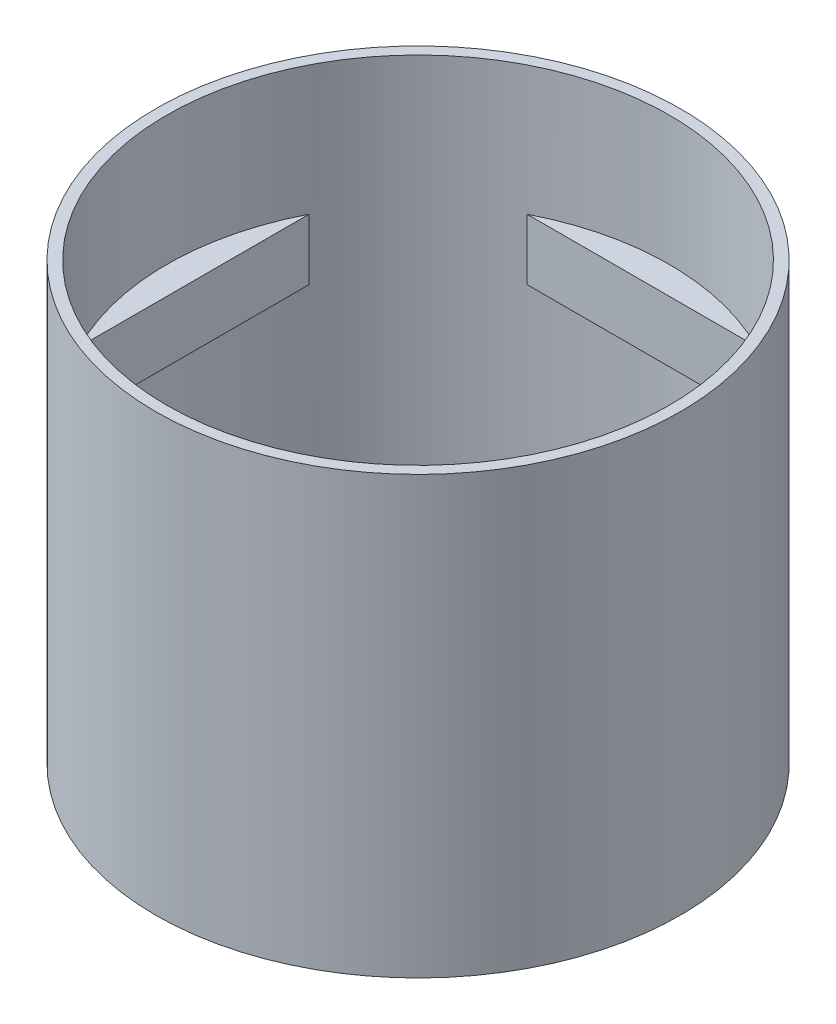
SolidWorks part; units mm, degrees
ref_plane "前基準面" through (0, 0, 0) normal (0, 0, 1) x (1, 0, 0)
ref_plane "上基準面" through (0, 0, 0) normal (0, 1, 0) x (1, 0, 0)
ref_plane "右基準面" through (0, 0, 0) normal (1, 0, 0) x (0, 0, -1)
sketch "草圖1" plane through (0, 0, 0) normal (0, 1, 0) x (1, 0, 0)
  line L0 (0, 78.355) -> (0, -92.3476) construction
  line L1 (-97.6496, 0) -> (95.3358, 0) construction
  line L3 (-34, 34) -> (34, 34) construction
  line L4 (-34, 34) -> (-34, -34) construction
  line L5 (-34, -34) -> (34, -34) construction
  line L6 (34, 34) -> (34, -34) construction
  line L7 (-34, 34) -> (34, -34) construction
  line L20 (45.5449, 45.5449) -> (-45.5449, -45.5449) construction
  circle A0 centre (0, 0) radius 72.25
  circle A1 centre (0, 0) radius 71
  circle A2 centre (0, 0) radius 68
  circle A4 centre (0, 0) radius 73 construction
  point P7 (0, 0)
  point P12 (-30, 30)
  point P14 (30, 30)
  point P17 (30, -30)
  point P18 (-30, -30)
  point P19 (0, 0)
  point P23 (-73, 0)
  point P24 (-72.25, 0)
  point P25 (-71, 0)
  point P26 (34, 0)
  point P27 (-34, 0)
  point P28 (-68, 0)
  dimension "D1" = 144.5
  dimension "D5" = 142
  dimension "D6" = 3
  dimension "D8" = 146
  dimension "D2" = 68
  dimension "D3" = 4
  dimension "D4" = 4
sketch "草圖4" plane through (0, 0, 0) normal (0, 0, 1) x (1, 0, 0)
  line L0 (-34, 0) -> (-34, 118)
  line L1 (73, 0) -> (-73, 0) construction
  line L3 (34, 0) -> (36.5756, 118)
  line L4 (36.5756, 118) -> (-34, 118)
  line L5 (-34, 0) -> (34, 0)
  line L6 (-34, 15) -> (34.3274, 15)
  line L7 (-34, 16.5) -> (34.3601, 16.5)
  line L8 (-34, 31.5) -> (34.6876, 31.5)
  line L9 (-34, 33) -> (34.7203, 33)
  line L10 (-34, 48) -> (35.0477, 48)
  line L11 (-34, 49.5) -> (35.0804, 49.5)
  line L12 (-34, 66.5) -> (35.4515, 66.5)
  line L13 (-34, 68) -> (35.4843, 68)
  line L14 (-34, 83) -> (35.8117, 83)
  line L15 (-34, 85) -> (35.8553, 85)
  line L16 (-34, 101.5) -> (36.2155, 101.5)
  line L17 (-34, 103) -> (36.2482, 103)
  line L18 (-72.25, 0) -> (-72.25, 145.0993)
  line L19 (-68, 0) -> (-68, 146.8435)
  line L20 (-30, 0) -> (-30, 145.404) construction
  line L21 (-31.5, 118) -> (-31.5, 124) construction
  line L22 (-31.5, 124) -> (-28.5, 124) construction
  line L23 (-28.5, 124) -> (-28.5, 118) construction
  line L24 (-34, 86.5) -> (35.8881, 86.5)
  line L25 (-34, 64.5) -> (35.4079, 64.5)
  point P40 (-30, 124)
  dimension "D1" = 1.5
  dimension "D2" = 15
  dimension "D3" = 1.5
  dimension "D4" = 1.5
  dimension "D5" = 1.5
  dimension "D6" = 15
  dimension "D7" = 15
  dimension "D8" = 15
  dimension "D9" = 2
  dimension "D10" = 15
  dimension "D11" = 1.5
  dimension "D12" = 15
  dimension "D13" = 15
  dimension "D14" = 3
  dimension "D15" = 6
  dimension "D16" = 1.5
  dimension "D17" = 83
  dimension "D18" = 2
  dimension "D19" = 118
sketch "草圖5" plane through (0, 0, 0) normal (0, 1, 0) x (1, 0, 0)
  line L0 (-60.5191, 11) -> (-50.0191, 11) construction
  line L1 (-50.0191, 11) -> (-50.0191, -11) construction
  line L2 (-50.0191, -11) -> (-60.5191, -11) construction
  line L3 (-60.5191, -11) -> (-60.5191, 11)
  line L4 (-60.5191, 8.25) -> (-70.5191, 8.25) construction
  line L6 (-70.5191, -8.25) -> (-60.5191, -8.25) construction
  line L7 (-97.6496, 0) -> (95.3358, 0) construction
  line L8 (-60.5191, 8.25) -> (-60.5191, -8.25) construction
  line L9 (-34, 34) -> (34, -34) construction
  line L10 (0, 0) -> (-19.3715, 0) construction
  line L12 (-70.5191, 8.25) -> (-70.5191, -8.25) construction
  line L13 (-60.5191, 8.25) -> (-60.5191, 31.0072)
  line L14 (-60.5191, -8.25) -> (-60.5191, -31.0072)
  line L15 (8.25, 60.5191) -> (8.25, 70.5191) construction
  line L16 (-8.25, 70.5191) -> (-8.25, 60.5191) construction
  line L17 (8.25, 60.5191) -> (31.0072, 60.5191)
  line L18 (-8.25, 60.5191) -> (-31.0072, 60.5191)
  line L19 (11, 60.5191) -> (11, 50.0191) construction
  line L20 (11, 50.0191) -> (-11, 50.0191) construction
  line L21 (-11, 50.0191) -> (-11, 60.5191) construction
  line L22 (-11, 60.5191) -> (11, 60.5191)
  line L23 (8.25, 60.5191) -> (-8.25, 60.5191) construction
  line L24 (8.25, 70.5191) -> (-8.25, 70.5191) construction
  line L25 (60.5191, -8.25) -> (70.5191, -8.25) construction
  line L26 (70.5191, 8.25) -> (60.5191, 8.25) construction
  line L27 (60.5191, -8.25) -> (60.5191, -31.0072)
  line L28 (60.5191, 8.25) -> (60.5191, 31.0072)
  line L29 (60.5191, -11) -> (50.0191, -11) construction
  line L30 (50.0191, -11) -> (50.0191, 11) construction
  line L31 (50.0191, 11) -> (60.5191, 11) construction
  line L32 (60.5191, 11) -> (60.5191, -11)
  line L33 (60.5191, -8.25) -> (60.5191, 8.25) construction
  line L34 (70.5191, -8.25) -> (70.5191, 8.25) construction
  line L35 (-8.25, -60.5191) -> (-8.25, -70.5191) construction
  line L36 (8.25, -70.5191) -> (8.25, -60.5191) construction
  line L37 (-8.25, -60.5191) -> (-31.0072, -60.5191)
  line L38 (8.25, -60.5191) -> (31.0072, -60.5191)
  line L39 (-11, -60.5191) -> (-11, -50.0191) construction
  line L40 (-11, -50.0191) -> (11, -50.0191) construction
  line L41 (11, -50.0191) -> (11, -60.5191) construction
  line L42 (11, -60.5191) -> (-11, -60.5191)
  line L43 (-8.25, -60.5191) -> (8.25, -60.5191) construction
  line L44 (-8.25, -70.5191) -> (8.25, -70.5191) construction
  circle A0 centre (0, 0) radius 68 construction
  circle A1 centre (0, 0) radius 72.25 construction
  arc A2 (-31.0072, 60.5191) -> (-60.5191, 31.0072) centre (0, 0) ccw
  circle A3 centre (0, 0) radius 68
  arc A5 (-60.5191, -31.0072) -> (-31.0072, -60.5191) centre (0, 0) ccw
  circle A6 centre (0, 0) radius 72.25
  arc A7 (60.5191, 31.0072) -> (31.0072, 60.5191) centre (0, 0) ccw
  circle A8 centre (0, 0) radius 71 construction
  circle A9 centre (0, 0) radius 71
  arc A12 (31.0072, -60.5191) -> (60.5191, -31.0072) centre (0, 0) ccw
  point P7 (-60.5191, 0)
  point P58 (0, 0)
  dimension "D1" = 10
  dimension "D2" = 10.5
  dimension "D3" = 22
  dimension "D4" = 16.5
  dimension "D5" = 4
extrude "填料-伸長1" add sketch "草圖1" along normal up to vertex (118 mm away) contours A1 A2 up to point (-34, 118, 0)
sketch "草圖15" plane through (0, 0, 0) normal (0, -1, 0) x (1, 0, 0)
  circle A0 centre (-30, 30) radius 1.5
  circle A1 centre (-30, 30) radius 3
  dimension "D1" = 3
  dimension "D2" = 6
sketch "草圖16" plane through (0, 0, 0) normal (0, -1, 0) x (-1, 0, 0)
  line L1 (-53.8073, 26.6906) -> (-37.8073, 26.6906)
  line L2 (-53.8073, 26.6906) -> (-53.8073, 14.4906)
  line L3 (-53.8073, 14.4906) -> (-37.8073, 14.4906)
  line L4 (-37.8073, 26.6906) -> (-37.8073, 14.4906)
  line L5 (-53.8073, 26.6906) -> (-37.8073, 14.4906) construction
  line L6 (-53.8073, 14.4906) -> (-37.8073, 26.6906) construction
  line L7 (-54.8073, 27.6906) -> (-36.8073, 27.6906)
  line L8 (-54.8073, 27.6906) -> (-54.8073, 13.4906)
  line L9 (-54.8073, 13.4906) -> (-36.8073, 13.4906)
  line L10 (-36.8073, 27.6906) -> (-36.8073, 13.4906)
  line L11 (-54.8073, 27.6906) -> (-36.8073, 13.4906) construction
  line L12 (-54.8073, 13.4906) -> (-36.8073, 27.6906) construction
  point P5 (-45.8073, 20.5906)
  dimension "D1" = 16
  dimension "D2" = 12.2
  dimension "D3" = 1
  dimension "D4" = 1
  dimension "D5" = 1
  dimension "D6" = 1
sketch "草圖17" plane through (0, 0, 0) normal (0, -1, 0) x (-1, 0, 0)
  circle A0 centre (-41.8475, 42.297) radius 8.5
  circle A1 centre (0, 0) radius 68 construction
  dimension "D1" = 17
extrude "填料-伸長9" add sketch "草圖5" along normal up to vertex (83 mm away) from vertex at 66.5 contours L37 A3 L38 L42 | L17 A3 L18 L22 | L13 A3 L14 L3 | L27 A3 L28 L32 starting at point (35.4515, 66.5, 0)
sketch "草圖18" plane through (-60.5191, 0, 0) normal (1, 0, 0) x (0, 0, -1)
  line L0 (0, 83) -> (0, 66.5) construction
  line L1 (-31.0072, 83) -> (31.0072, 83) construction
  line L2 (-31.0072, 66.5) -> (31.0072, 66.5) construction
  circle A0 centre (0, 74.75) radius 7.0619
  point P2 (0, 94.75)
